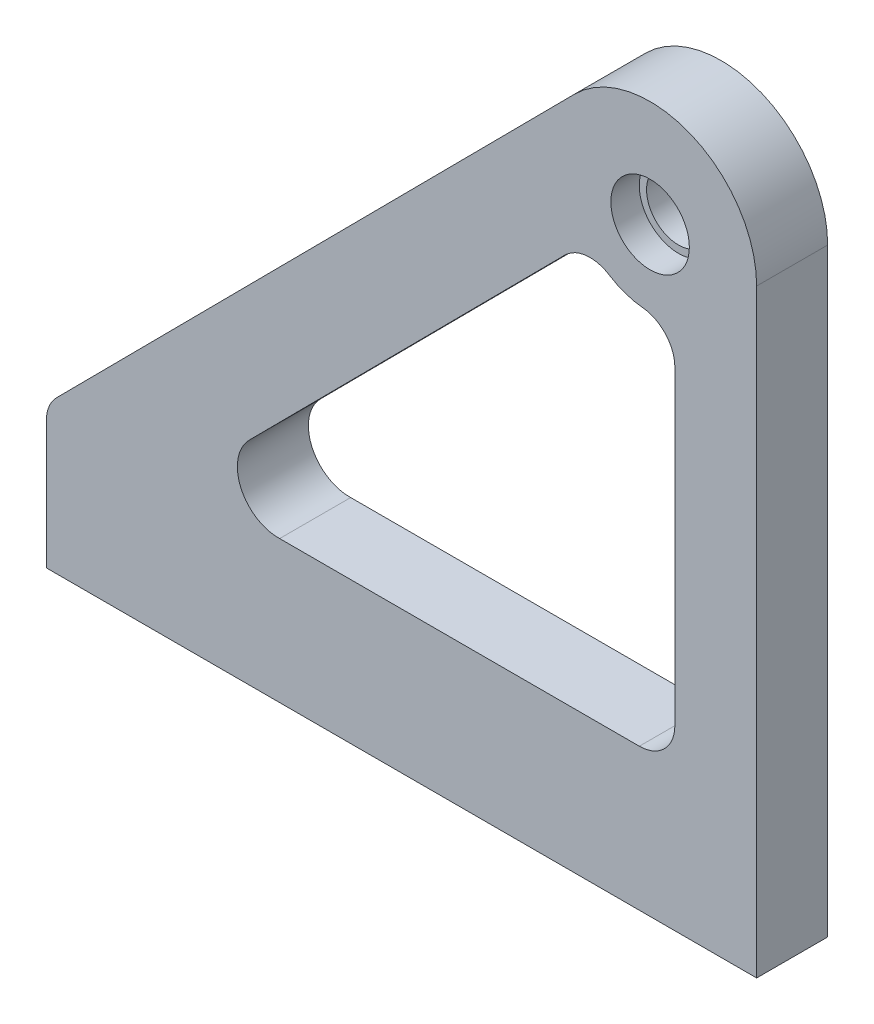
SolidWorks part; units mm, degrees
material "ABS"
ref_plane "Front Plane" through (0, 0, 0) normal (0, 0, 1) x (1, 0, 0)
ref_plane "Top Plane" through (0, 0, 0) normal (0, 1, 0) x (1, 0, 0)
ref_plane "Right Plane" through (0, 0, 0) normal (1, 0, 0) x (0, 0, -1)
sketch "Sketch2" plane through (0, 0, 0) normal (0, 0, 1) x (1, 0, 0)
  line L0 (-88.6256, -17.4255) -> (11.3744, -17.4255)
  line L6 (-88.6256, -17.4255) -> (-88.6256, 0.5271)
  line L7 (11.3744, -17.4255) -> (11.3744, 2.5745)
  line L12 (11.3744, 2.5745) -> (11.3744, 66.9385)
  line L13 (-87.1745, 4.0492) -> (-14.2723, 77.5049)
  line L17 (-60.0516, 12.4463) -> (-15.6209, 57.2143)
  line L37 (-0.142, 51.3017) -> (-0.142, 7.5745)
  line L38 (-5.142, 2.5745) -> (-55.7765, 2.5745)
  arc A10 (11.3744, 66.9385) -> (-14.2723, 77.5049) centre (-3.6256, 66.9385) ccw
  circle A11 centre (-3.6256, 66.9385) radius 5.525
  arc A12 (-9.3838, 57.908) -> (-4.6594, 56.2784) centre (-3.6256, 66.9385) ccw
  arc A13 (-88.6256, 0.5271) -> (-87.1745, 4.0492) centre (-83.6256, 0.5271) cw
  arc A14 (-15.6209, 57.2143) -> (-9.3838, 57.908) centre (-12.072, 53.6921) cw
  arc A15 (-0.142, 51.3017) -> (-4.6594, 56.2784) centre (-5.142, 51.3017) ccw
  arc A17 (-55.7765, 2.5745) -> (-60.0516, 12.4463) centre (-55.9397, 8.3654) cw
  arc A25 (-0.142, 7.5745) -> (-5.142, 2.5745) centre (-5.142, 7.5745) cw
  dimension "D2" = 5
  dimension "D3" = 11.05
  dimension "D8" = 5
  dimension "D1" = 100
extrude "Boss-Extrude1" add sketch "Sketch2" along normal blind 10 contours L0
sketch "Sketch4" plane through (0, -17.4255, 0) normal (0, -1, 0) x (1, 0, 0)
  line L1 (-88.6256, 10) -> (11.3744, 10) construction
  line L2 (-88.6256, 0) -> (11.3744, 0) construction
  line L3 (-78.6256, 2.5) -> (-78.6256, 12.5) construction
  line L4 (-88.6256, 10) -> (-88.6256, 0) construction
  circle A0 centre (-78.6256, 12.5) radius 5
  circle A1 centre (-78.6256, 2.5) radius 5.125
  circle A2 centre (1.3744, 2.5) radius 5.125
  circle A3 centre (1.3744, 12.5) radius 5
  dimension "D1" = 10
  dimension "D2" = 2.5
  dimension "D3" = 2.5
  dimension "D4" = 10.25
  dimension "D5" = 10
  dimension "D6" = 2
extrude "Cut-Extrude2" cut sketch "Sketch4" against normal blind 7 contours A1 | A2
sketch "Sketch5" plane through (0, 0, 0) normal (0, 0, -1) x (-1, 0, 0)
  circle A0 centre (3.6256, 66.9385) radius 5.525
  circle A1 centre (3.6256, 66.9385) radius 4.5
  dimension "D1" = 9
extrude "Boss-Extrude4" add sketch "Sketch5" against normal blind 6 contours A1
